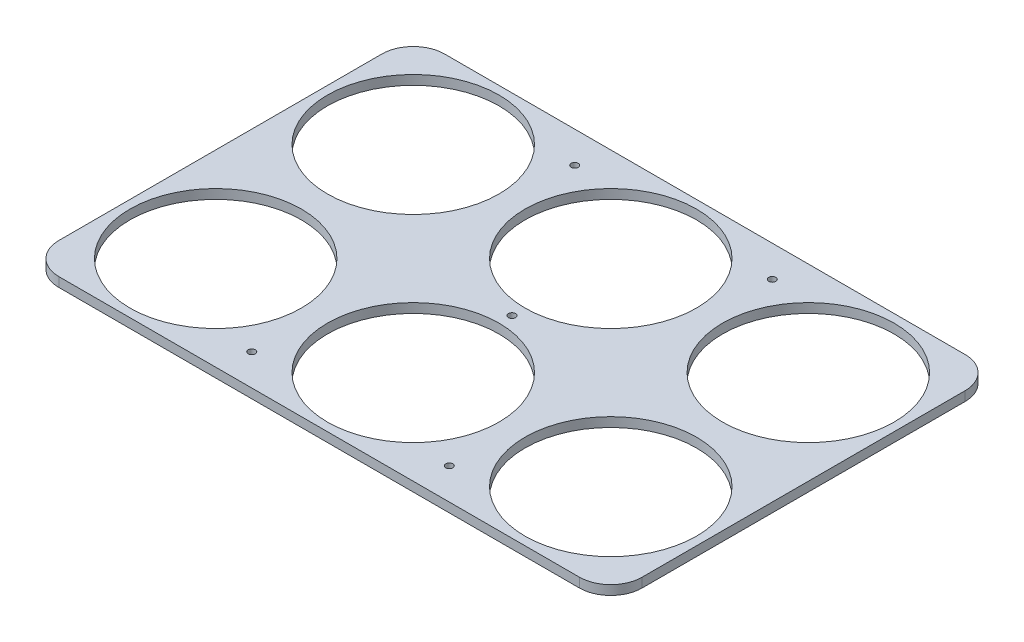
SolidWorks part; units mm, degrees
material "6063-O"
ref_plane "Front" through (0, 0, 0) normal (0, 0, 1) x (1, 0, 0)
ref_plane "Top" through (0, 0, 0) normal (0, 1, 0) x (1, 0, 0)
ref_plane "Right" through (0, 0, 0) normal (1, 0, 0) x (0, 0, -1)
sketch "Sketch1" plane through (0, 0, 0) normal (0, 1, 0) x (1, 0, 0)
  line L1 (93, 61.5) -> (-93, 61.5)
  line L2 (93, 61.5) -> (93, -61.5)
  line L3 (93, -61.5) -> (-93, -61.5)
  line L4 (-93, 61.5) -> (-93, -61.5)
  line L5 (93, 61.5) -> (-93, -61.5) construction
  line L6 (93, -61.5) -> (-93, 61.5) construction
  circle A0 centre (-63, 31.5) radius 27.35
  circle A1 centre (0, 31.5) radius 27.35
  circle A2 centre (63, 31.5) radius 27.35
  circle A4 centre (0, -31.5) radius 27.35
  circle A5 centre (63, -31.5) radius 27.35
  circle A10 centre (-63, -31.5) radius 27.35
  point P0 (0, 0)
  dimension "D3" = 54.7
  dimension "D6" = 30
  dimension "D7" = 30
  dimension "D1" = 30
  dimension "D8" = 123
  dimension "D2" = 30
  dimension "D9" = 30
  dimension "D10" = 186
  dimension "D4" = 3
  dimension "D5" = 2
extrude "Boss-Extrude1" add sketch "Sketch1" along normal blind 3
fillet "Fillet1" radius 10 4 edges at (93, 1.5, -61.5) (93, 1.5, 61.5) (-93, 1.5, 61.5) (-93, 1.5, -61.5)
hole_wizard "Tap Drill for #4-40 Tap1" positions "Sketch2" profile "Sketch3" hole size "#4-40" standard "ANSI Inch" end condition through all
sketch "Sketch2" plane through (0, 3, 0) normal (0, 1, 0) x (1, 0, 0)
  line L6 (-83, -61.5) -> (83, -61.5) construction
  line L7 (83, 61.5) -> (-83, 61.5) construction
  line L8 (93, -51.5) -> (93, 51.5) construction
  line L9 (-93, 51.5) -> (-93, -51.5) construction
  point P2 (0, 0)
  point P7 (31.5, 51.5)
  point P9 (-31.5, 51.5)
  point P11 (-31.5, -51.5)
  point P13 (31.5, -51.5)
  dimension "D3" = 61.5
  dimension "D1" = 10
  dimension "D2" = 10
  dimension "D4" = 61.5
sketch "Sketch3" plane through (0, 3, 0) normal (1, 0, 0) x (0, 0, 1)
  line L0 (0, 0) -> (0, 3)
  line L1 (0, 3) -> (1.1303, 3)
  line L2 (1.1303, 3) -> (1.1303, 0)
  line L5 (1.1303, 0) -> (0, 0)
  line L11 (0, -6.35) -> (0, 107.95) construction
  dimension "Thru Hole Dia." = 2.2606
  dimension "Thru Hole Depth" = 3
equation "\"D9@Sketch1\"=\"D2@Sketch1\""
